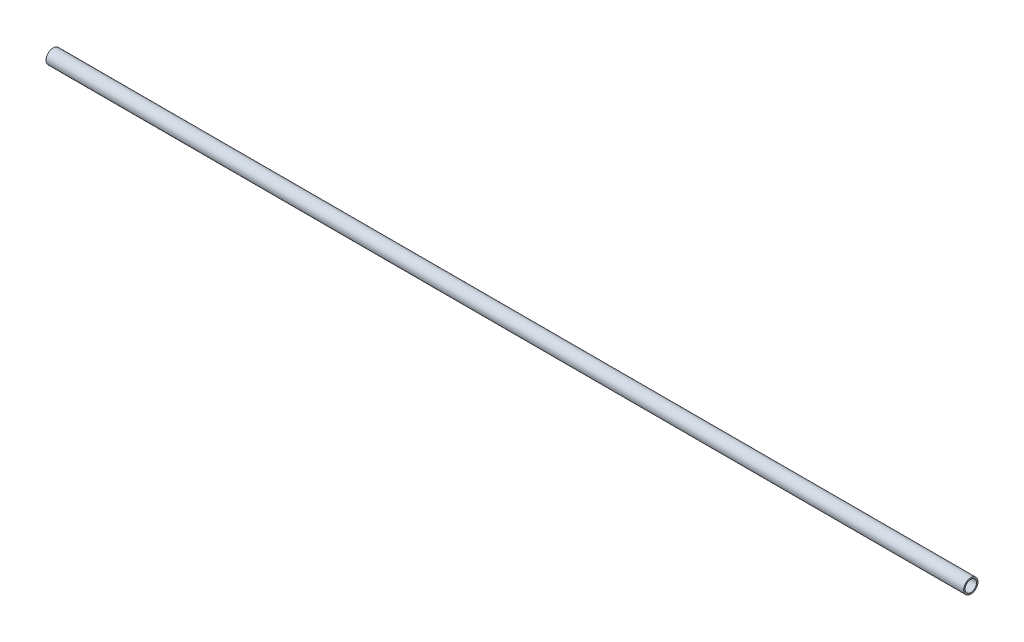
SolidWorks part; units mm, degrees
ref_plane "Front" through (0, 0, 0) normal (0, 0, 1) x (1, 0, 0)
ref_plane "Top" through (0, 0, 0) normal (0, 1, 0) x (1, 0, 0)
ref_plane "Right" through (0, 0, 0) normal (1, 0, 0) x (0, 0, -1)
sketch "Skizze1" plane through (0, 0, 0) normal (1, 0, 0) x (0, 0, -1)
  circle A0 centre (0, 0) radius 1
  circle A1 centre (0, 0) radius 1.25
  dimension "D1" = 2.5
  dimension "D2" = 2
extrude "Aufsatz-Linear austragen1" add sketch "Skizze1" along normal mid plane 160
